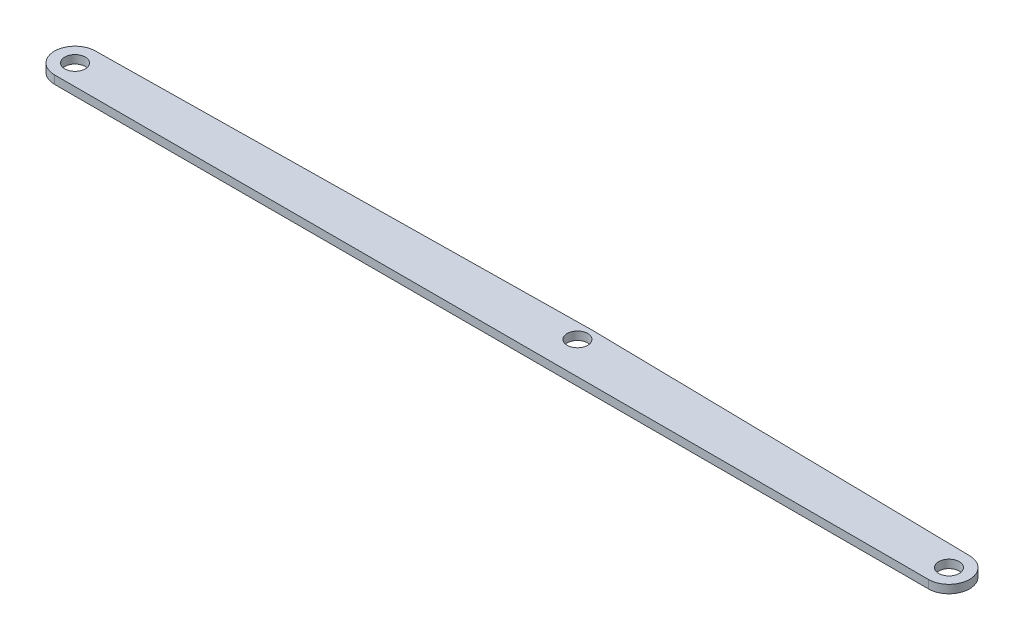
SolidWorks part; units mm, degrees
ref_plane "Front Plane" through (0, 0, 0) normal (0, 0, 1) x (1, 0, 0)
ref_plane "Top Plane" through (0, 0, 0) normal (0, 1, 0) x (1, 0, 0)
ref_plane "Right Plane" through (0, 0, 0) normal (1, 0, 0) x (0, 0, -1)
sketch "Sketch2" plane through (0, 0, 0) normal (0, 1, 0) x (1, 0, 0)
  line L0 (0, 0) -> (0, -12.7) construction
  line L1 (0, 0) -> (0, 12.7) construction
  line L2 (0, 0) -> (12.7, 0) construction
  line L3 (0, 0) -> (-539.8, 0) construction
  line L4 (-539.8, 0) -> (-552.5, 0) construction
  line L5 (-539.8, 0) -> (-539.8, 12.7) construction
  line L6 (-539.8, 0) -> (-539.8, -12.7) construction
  line L7 (-539.8, -12.7) -> (0, -12.7)
  line L9 (-539.8, 0) -> (-236.7877, 7.2923) construction
  line L10 (-539.8, 12.7) -> (-236.9172, 16.8164)
  line L11 (0, 12.7) -> (-236.6221, 16.8159)
  circle A0 centre (0, 0) radius 6.35
  arc A1 (0, 12.7) -> (0, -12.7) centre (0, 0) cw
  circle A2 centre (-539.8, 0) radius 6.35
  arc A3 (-539.8, -12.7) -> (-539.8, 12.7) centre (-539.8, 0) cw
  circle A5 centre (-236.7877, 7.2923) radius 6.35
  arc A6 (-236.6221, 16.8159) -> (-236.9172, 16.8164) centre (-236.7877, 7.2923) ccw
  point P13 (0, 0)
  point P15 (0, 0)
  dimension "D1" = 12.7
  dimension "D6" = 12.7
  dimension "D9" = 12.7
  dimension "D11" = 19.05
  dimension "D2" = 12.7
  dimension "D3" = 12.7
  dimension "D4" = 12.7
  dimension "D5" = 539.8
  dimension "D7" = 12.7
  dimension "D8" = 303.1
  dimension "D10" = 1.379
extrude "Boss-Extrude1" add sketch "Sketch2" along normal blind 5.08
